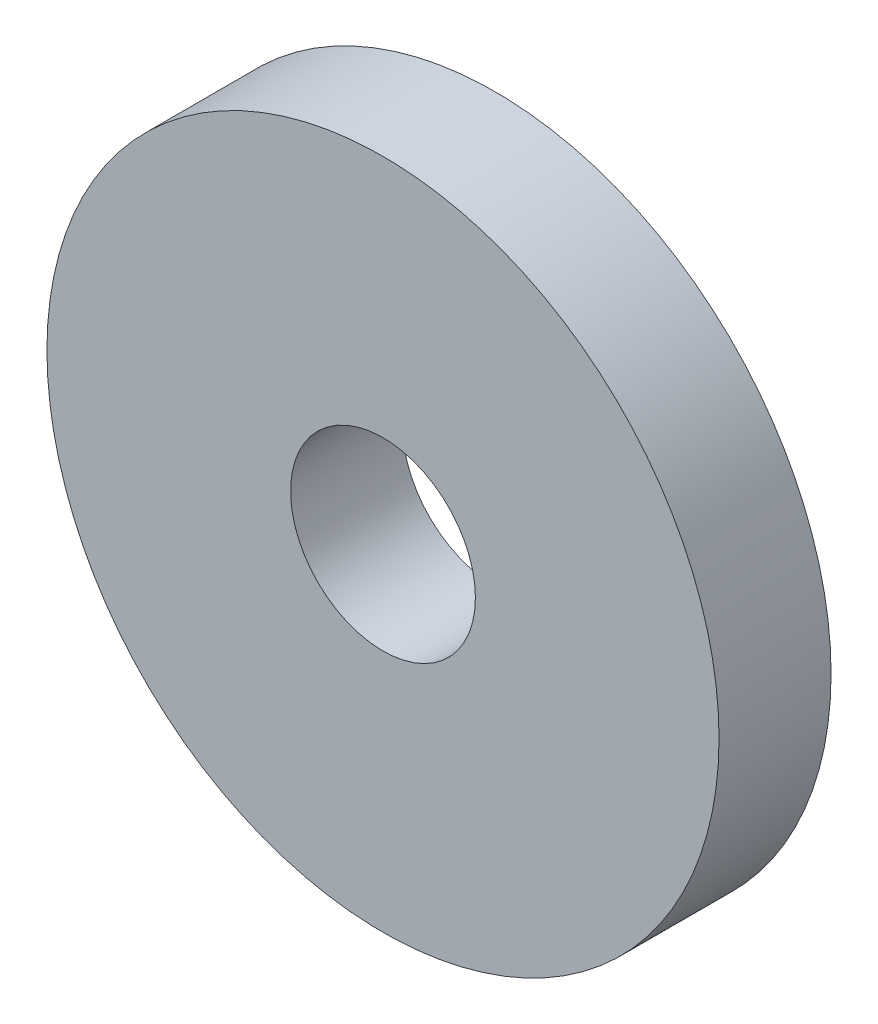
SolidWorks part; units mm, degrees
ref_plane "Front Plane" through (0, 0, 0) normal (0, 0, 1) x (1, 0, 0)
ref_plane "Top Plane" through (0, 0, 0) normal (0, 1, 0) x (1, 0, 0)
ref_plane "Right Plane" through (0, 0, 0) normal (1, 0, 0) x (0, 0, -1)
sketch "Sketch1" plane through (0, 0, 0) normal (0, 0, 1) x (1, 0, 0)
  circle A0 centre (0, 0) radius 3.3
  circle A1 centre (0, 0) radius 12
  dimension "D1" = 24
  dimension "D2" = 6.6
extrude "Boss-Extrude1" add sketch "Sketch1" along normal mid plane 4
